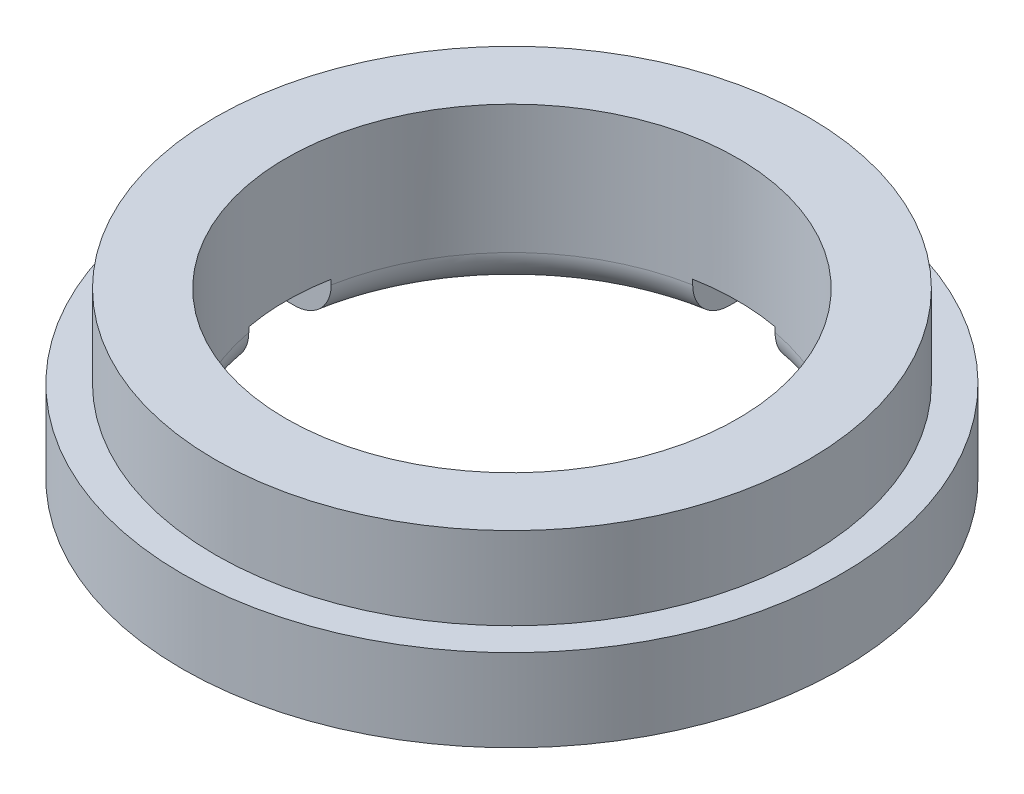
SolidWorks part; units mm, degrees
material "1060 Alloy"
ref_plane "Front Plane" through (0, 0, 0) normal (0, 0, 1) x (1, 0, 0)
ref_plane "Top Plane" through (0, 0, 0) normal (0, 1, 0) x (1, 0, 0)
ref_plane "Right Plane" through (0, 0, 0) normal (1, 0, 0) x (0, 0, -1)
sketch "Sketch1" plane through (0, 0, 0) normal (0, 1, 0) x (1, 0, 0)
  circle A0 centre (0, 0) radius 50.8
  circle A1 centre (0, 0) radius 34.798
  dimension "D1" = 101.6
  dimension "D2" = 69.596
extrude "Boss-Extrude1" add sketch "Sketch1" along normal blind 12.7
sketch "Sketch2" plane through (0, 12.7, 0) normal (0, 1, 0) x (1, 0, 0)
  circle A0 centre (0, 0) radius 34.798 construction
  circle A1 centre (0, 0) radius 34.798
  circle A2 centre (0, 0) radius 45.72
  dimension "D1" = 91.44
extrude "Boss-Extrude2" add sketch "Sketch2" along normal blind 12.7
fillet "Fillet1" radius 5.588 1 edges at (0, 0, 34.798)
sketch "Sketch3" plane through (0, 0, 0) normal (0, -1, 0) x (1, 0, 0)
  line L0 (0, 0) -> (34.925, 0) construction
  line L2 (41.275, -6.35) -> (28.575, -6.35)
  line L3 (41.275, -6.35) -> (41.275, 6.35)
  line L4 (41.275, 6.35) -> (28.575, 6.35)
  line L5 (28.575, -6.35) -> (28.575, 6.35)
  line L6 (34.925, 6.35) -> (34.925, -6.35) construction
  line L7 (41.275, 0) -> (28.575, 0) construction
  circle A1 centre (0, 0) radius 50.8 construction
  dimension "D1" = 12.7
  dimension "D2" = 9.525
  dimension "D3" = 12.7
extrude "Cut-Extrude1" cut sketch "Sketch3" against normal blind 6.35
pattern_circular "CirPattern1" count 4 over 360 about axis through (0, 0, 0) along (0, 1, 0) of "Cut-Extrude1"
